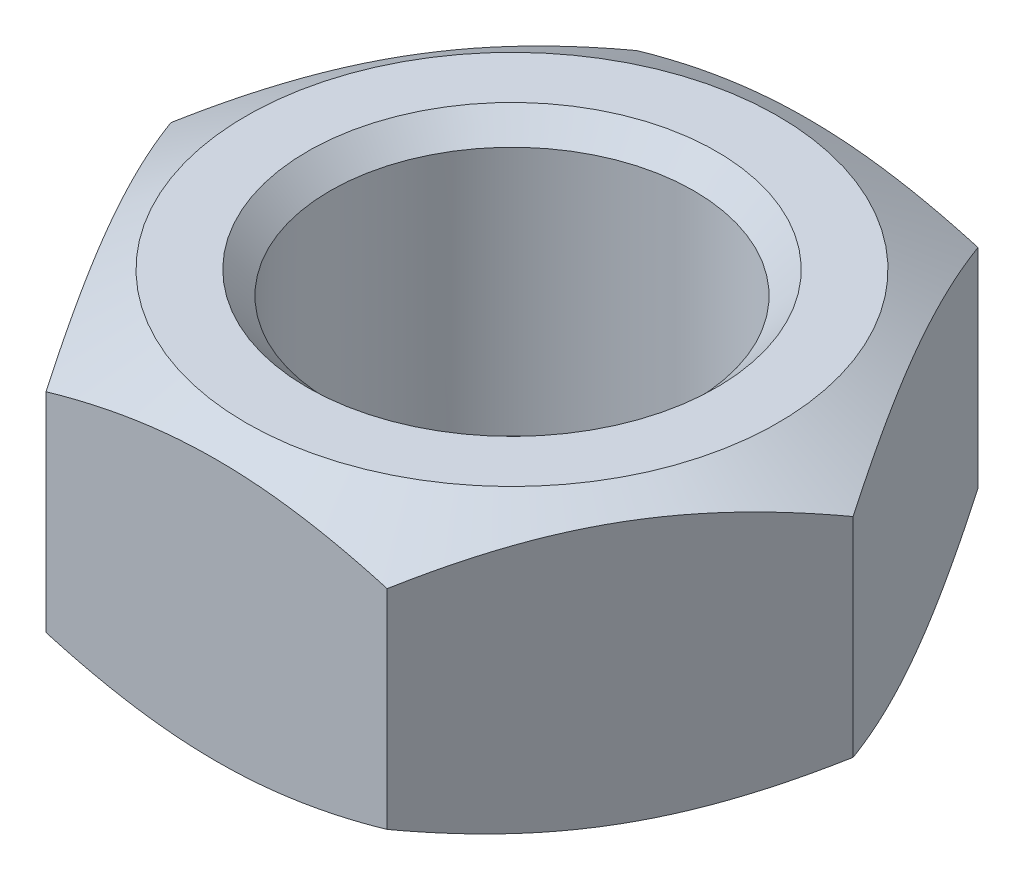
SolidWorks part; units mm, degrees
ref_plane "Спереди" through (0, 0, 0) normal (0, 0, 1) x (1, 0, 0)
ref_plane "Сверху" through (0, 0, 0) normal (0, 1, 0) x (1, 0, 0)
ref_plane "Справа" through (0, 0, 0) normal (1, 0, 0) x (0, 0, -1)
sketch "Эскиз1" plane through (0, 0, 0) normal (0, 1, 0) x (1, 0, 0)
  line L0 (-3.7528, 6.5) -> (3.7528, 6.5)
  line L1 (3.7528, 6.5) -> (7.5056, 0)
  line L2 (7.5056, 0) -> (3.7528, -6.5)
  line L3 (3.7528, -6.5) -> (-3.7528, -6.5)
  line L4 (-3.7528, -6.5) -> (-7.5056, 0)
  line L5 (-7.5056, 0) -> (-3.7528, 6.5)
  dimension "D5" = 6.5
  dimension "D2" = 120
  dimension "D3" = 120
  dimension "D4" = 120
  dimension "D6" = 6.5
  dimension "D7" = 6.5
  dimension "D8" = 6.5
  dimension "D9" = 6.5
  dimension "D10" = 120
  dimension "D11" = 6.5
extrude "Вытянуть1" add sketch "Эскиз1" against normal blind 6.5
sketch "Эскиз5" plane through (0, -6.5, 0) normal (0, -1, 0) x (1, 0, 0)
  circle A0 centre (0, 0) radius 4
  dimension "D1" = 8
extrude "Вырез-Вытянуть1" cut sketch "Эскиз5" against normal through all
ref_axis "Ось1" through (0, 0, 0) along (0, -1, 0)
ref_plane "Плоскость1" through (0, 0, 0) normal (0, 0, 1) x (1, 0, 0)
sketch "Эскиз4" plane through (0, 0, 0) normal (0, 0, 1) x (1, 0, 0)
  line L0 (-7.5056, -0.9558) -> (-5.85, 0)
  line L1 (-7.5056, -6.5) -> (-7.5056, 0) construction
  line L2 (-7.5056, 0) -> (-3.7528, 0) construction
  line L3 (-5.85, 0) -> (-7.5056, 0)
  line L4 (-7.5056, 0) -> (-7.5056, -0.9558)
  line L5 (-7.5056, -5.5442) -> (-5.85, -6.5)
  line L6 (-7.5056, -6.5) -> (-3.7528, -6.5) construction
  line L7 (-5.85, -6.5) -> (-7.5056, -6.5)
  line L8 (-7.5056, -6.5) -> (-7.5056, -5.5442)
  line L9 (0, 0) -> (0, -6.5) construction
  dimension "D1" = 5.85
  dimension "D2" = 30
  dimension "D3" = 5.85
  dimension "D4" = 30
revolve "Вырез-Повернуть1" cut sketch "Эскиз4" angle 360 about axis through (0, 0, 0) along (0, -1, 0)
chamfer "Фаска1" distance 0.5 angle 45 2 edges at (0, -6.5, -4) (0, 0, -4)
